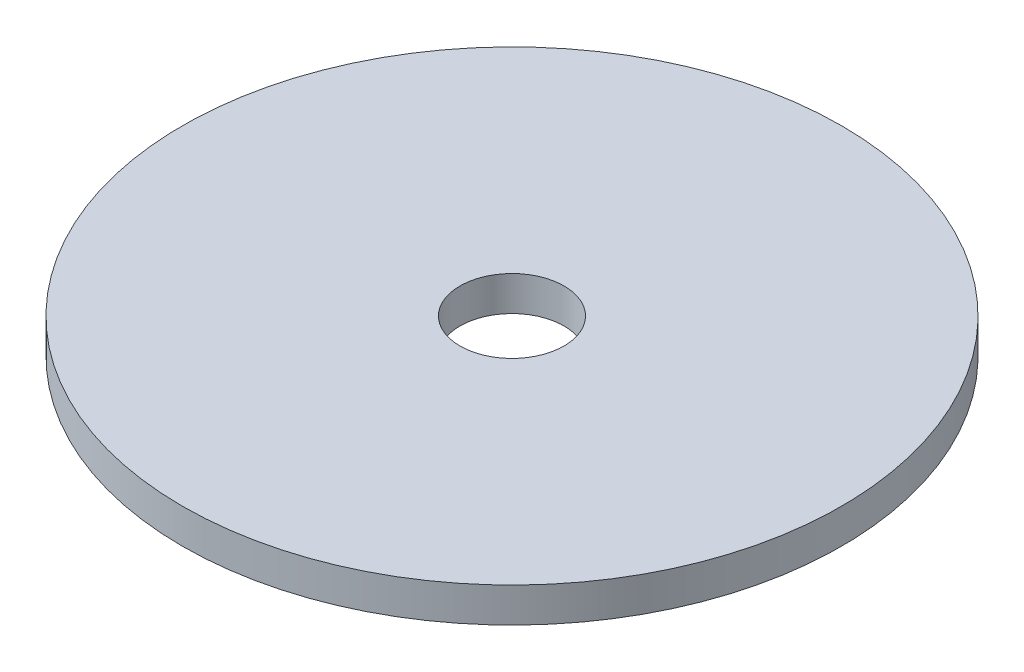
SolidWorks part; units mm, degrees
ref_plane "Front Plane" through (0, 0, 0) normal (0, 0, 1) x (1, 0, 0)
ref_plane "Top Plane" through (0, 0, 0) normal (0, 1, 0) x (1, 0, 0)
ref_plane "Right Plane" through (0, 0, 0) normal (1, 0, 0) x (0, 0, -1)
sketch "Sketch2" plane through (0, 0, 0) normal (0, 1, 0) x (1, 0, 0)
  line L0 (4.6435, -1) -> (-4.6435, -1)
  line L1 (-3.2113, 3.5) -> (3.2113, 3.5)
  line L2 (0, 0) -> (0, 4.75) construction
  circle A0 centre (0, 0) radius 0.75
  circle A1 centre (0, 0) radius 4.75
  circle A2 centre (-2.5, 2) radius 1.125
  circle A3 centre (2.5, 2) radius 1.125
  dimension "D1" = 1.5
  dimension "D2" = 9.5
  dimension "D5" = 2.25
  dimension "D3" = 1
  dimension "D4" = 3.5
  dimension "D6" = 2
  dimension "D7" = 2.5
extrude "Boss-Extrude1" add sketch "Sketch2" against normal blind 0.5
